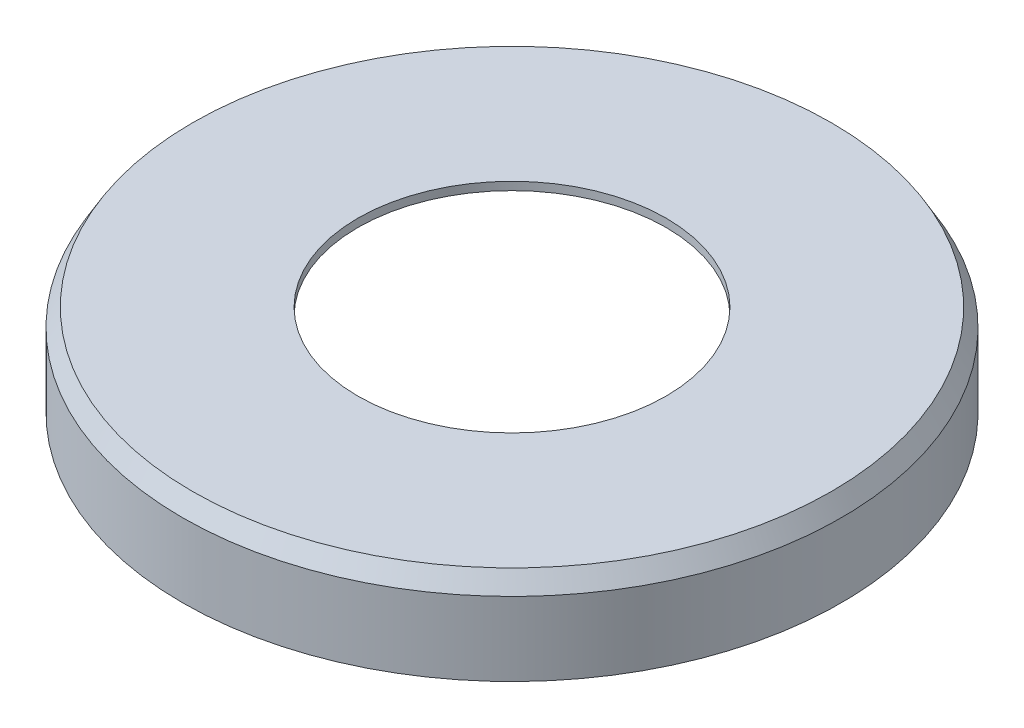
SolidWorks part; units mm, degrees
ref_plane "前视基准面" through (0, 0, 0) normal (0, 0, 1) x (1, 0, 0)
ref_plane "上视基准面" through (0, 0, 0) normal (0, 1, 0) x (1, 0, 0)
ref_plane "右视基准面" through (0, 0, 0) normal (1, 0, 0) x (0, 0, -1)
sketch "草图1" plane through (0, 0, 0) normal (0, 1, 0) x (1, 0, 0)
  circle A0 centre (0, 0) radius 28.5
  circle A1 centre (0, 0) radius 32.5
  dimension "D1" = 57
  dimension "D2" = 4
extrude "凸台-拉伸1" add sketch "草图1" along normal blind 7
sketch "草图2" plane through (0, 7, 0) normal (0, 1, 0) x (1, 0, 0)
  circle A0 centre (0, 0) radius 32.5
  circle A1 centre (0, 0) radius 32.5 construction
extrude "凸台-拉伸2" add sketch "草图2" along normal blind 2
sketch "草图3" plane through (0, 7, 0) normal (0, -1, 0) x (1, 0, 0)
  line L0 (0, 0) -> (29.25, 0) construction
  circle A3 centre (0, 0) radius 29.25
  dimension "D1" = 58.5
extrude "切除-拉伸1" cut sketch "草图3" along normal up to surface (7 mm away) up to face at (0, 0, 32.5)
sketch "草图4" plane through (0, 7, 0) normal (0, -1, 0) x (1, 0, 0)
  line L0 (28.2533, 7.5705) -> (27.5289, 7.3763) construction
  line L1 (0, 0) -> (32.5, 0) construction
  line L2 (28.2533, -7.5705) -> (27.5289, -7.3763) construction
  arc A1 (28.0499, -8.2924) -> (27.5289, -7.3763) centre (28.2533, -7.5705) cw
  circle A2 centre (0, 0) radius 28.5 construction
  circle A3 centre (0, 0) radius 29.25 construction
  circle A4 centre (0, 0) radius 32.5 construction
  arc A5 (27.5289, 7.3763) -> (27.5289, -7.3763) centre (0, 0) cw
  arc A6 (28.0499, 8.2924) -> (27.5289, 7.3763) centre (28.2533, 7.5705) ccw
  circle A7 centre (0, 0) radius 29.25 construction
  arc A8 (28.0499, -8.2924) -> (28.0499, 8.2924) centre (0, 0) ccw
  dimension "D1" = 57
  dimension "D2" = 15
extrude "凸台-拉伸3" add sketch "草图4" along normal up to surface (7 mm away) up to face at (0, 0, 29.25)
pattern_circular "阵列(圆周)1" count 3 over 360 about axis through (0, 0, 0) along (0, 1, 0) of "凸台-拉伸3"
chamfer "倒角1" distance 1 angle 60 1 edges at (0, 9, 32.5)
sketch "草图5" plane through (0, 7, 0) normal (0, -1, 0) x (1, 0, 0)
  circle A0 centre (0, 0) radius 15.2
  dimension "D1" = 30.4
extrude "切除-拉伸2" cut sketch "草图5" against normal through all
sketch "草图6" plane through (0, 7, 0) normal (0, -1, 0) x (1, 0, 0)
  circle A0 centre (0, 0) radius 18
  dimension "D1" = 36
extrude "切除-拉伸3" cut sketch "草图6" against normal blind 1.2
